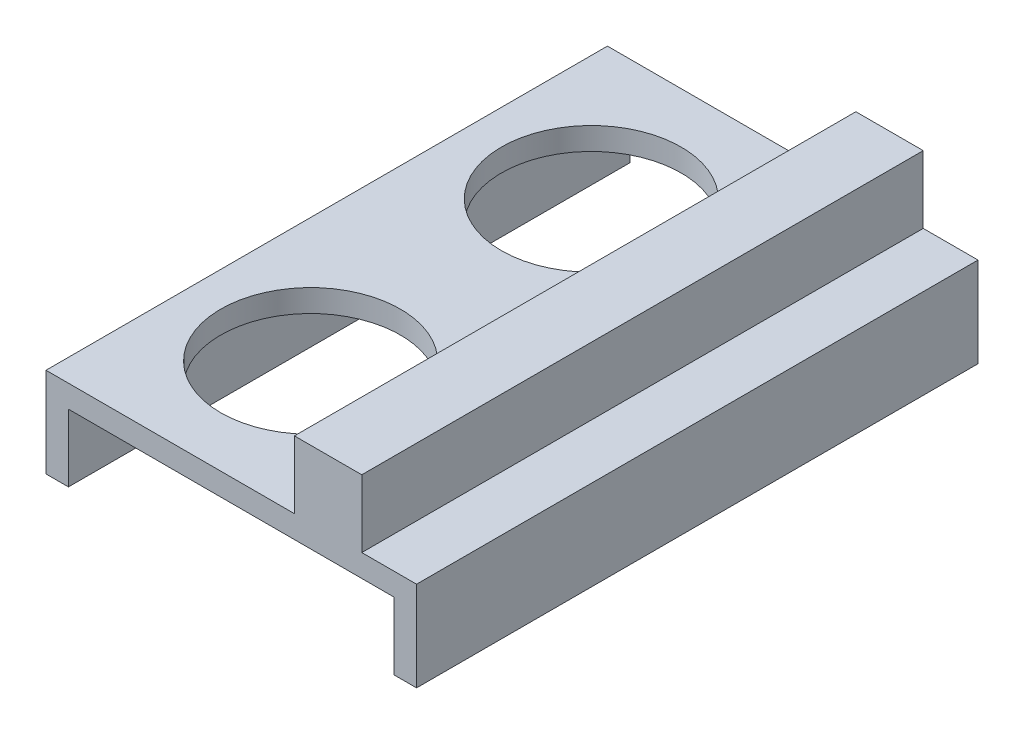
SolidWorks part; units mm, degrees
ref_plane "Front Plane" through (0, 0, 0) normal (0, 0, 1) x (1, 0, 0)
ref_plane "Top Plane" through (0, 0, 0) normal (0, 1, 0) x (1, 0, 0)
ref_plane "Right Plane" through (0, 0, 0) normal (1, 0, 0) x (0, 0, -1)
sketch "Sketch1" plane through (0, 0, 0) normal (0, 1, 0) x (1, 0, 0)
  line L1 (-29.5797, 18.6353) -> (3.4203, 18.6353)
  line L2 (-29.5797, 18.6353) -> (-29.5797, -31.3647)
  line L3 (-29.5797, -31.3647) -> (3.4203, -31.3647)
  line L4 (3.4203, 18.6353) -> (3.4203, -31.3647)
extrude "Boss-Extrude1" add sketch "Sketch1" along normal blind 2
sketch "Sketch2" plane through (0, 0, 0) normal (0, -1, 0) x (1, 0, 0)
  line L0 (3.4203, -18.6353) -> (-29.5797, -18.6353) construction
  line L1 (-29.5797, 31.3647) -> (-27.5797, 31.3647)
  line L2 (-29.5797, 31.3647) -> (-29.5797, -18.6353)
  line L3 (-29.5797, -18.6353) -> (-27.5797, -18.6353)
  line L4 (-27.5797, 31.3647) -> (-27.5797, -18.6353)
  line L6 (3.4203, 31.3647) -> (1.4203, 31.3647)
  line L7 (3.4203, 31.3647) -> (3.4203, -18.6353)
  line L8 (3.4203, -18.6353) -> (1.4203, -18.6353)
  line L9 (1.4203, 31.3647) -> (1.4203, -18.6353)
extrude "Boss-Extrude2" add sketch "Sketch2" along normal blind 6
sketch "Sketch3" plane through (0, 2, 0) normal (0, 1, 0) x (1, 0, 0)
  line L0 (-4.4569, -6.3647) -> (-1.4569, -6.3647)
  line L1 (-4.4569, -6.3647) -> (-7.4569, -6.3647)
  line L2 (-1.4569, -6.3647) -> (-1.4569, -31.3647)
  line L3 (-29.5797, -31.3647) -> (3.4203, -31.3647) construction
  line L4 (-1.4569, -31.3647) -> (-7.4569, -31.3647)
  line L5 (-7.4569, -31.3647) -> (-7.4569, -6.3647)
  line L6 (-7.4569, -6.3647) -> (-7.4569, 18.6353)
  line L7 (3.4203, 18.6353) -> (-29.5797, 18.6353) construction
  line L8 (-7.4569, 18.6353) -> (-1.4569, 18.6353)
  line L9 (-1.4569, 18.6353) -> (-1.4569, -6.3647)
  line M5 (-29.5797, -31.3647) -> (3.4203, -31.3647)
  line M7 (3.4203, 18.6353) -> (-29.5797, 18.6353)
extrude "Boss-Extrude3" add sketch "Sketch3" along normal blind 6 contours L5 L2 L0 L1 M5 | L9 L6 L1 L0 M7
sketch "Sketch4" plane through (0, 2, 0) normal (0, 1, 0) x (1, 0, 0)
  line L0 (-18.5183, -6.3647) -> (-18.5183, 18.6353)
  line L2 (-29.5797, -31.3647) -> (-7.4569, -31.3647) construction
  line L3 (-18.5183, -6.3647) -> (-18.5183, -31.3647)
  line L4 (-7.4569, 18.6353) -> (-29.5797, 18.6353) construction
  circle A0 centre (-18.5183, -18.8647) radius 8
  circle A1 centre (-18.5183, 6.1353) radius 8
extrude "Cut-Extrude1" cut sketch "Sketch4" against normal blind 6 contours L3 A0 | L3 A0 | L0 A1 | L0 A1
